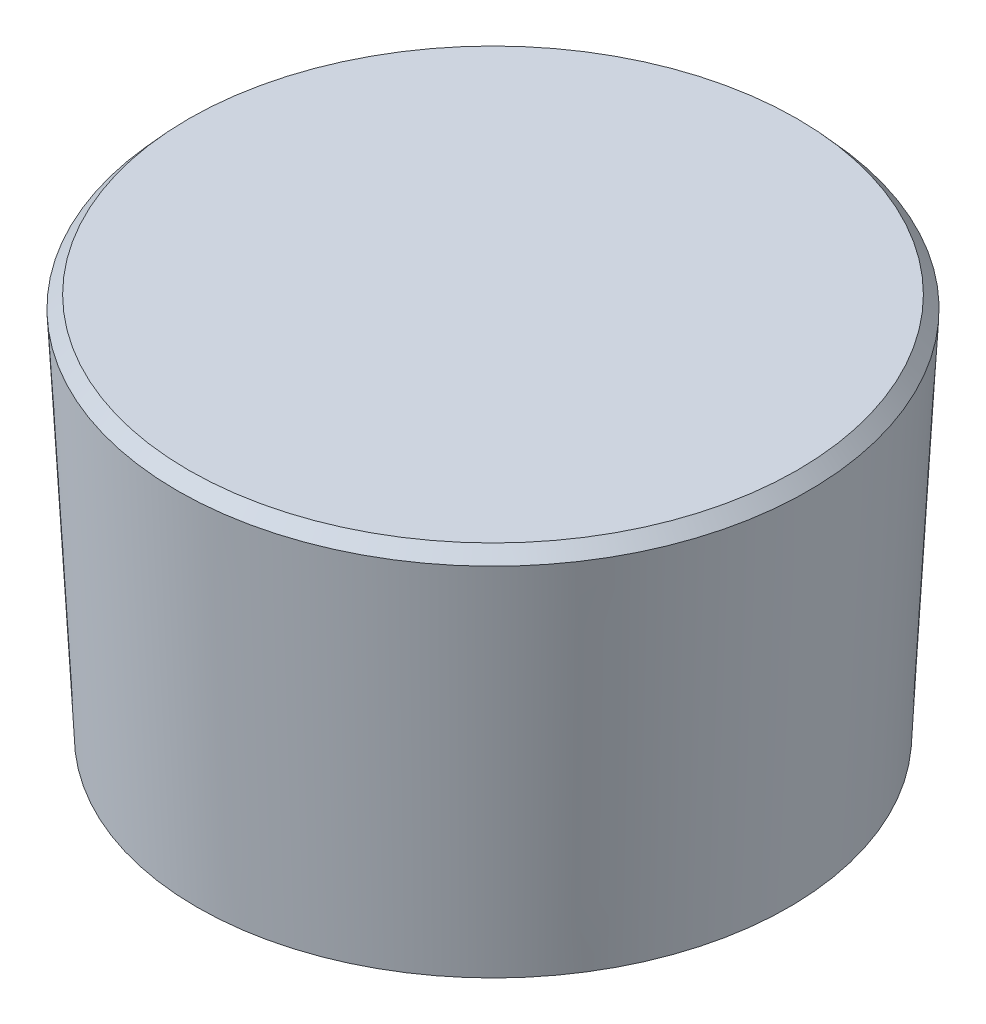
SolidWorks part; units mm, degrees
ref_plane "Front" through (0, 0, 0) normal (0, 0, 1) x (1, 0, 0)
ref_plane "Top" through (0, 0, 0) normal (0, 1, 0) x (1, 0, 0)
ref_plane "Right" through (0, 0, 0) normal (1, 0, 0) x (0, 0, -1)
sketch "Sketch1" plane through (0, 0, 0) normal (0, 1, 0) x (1, 0, 0)
  circle A0 centre (0, 0) radius 5.122
  dimension "D1" = 10.244
extrude "Extrude1" add sketch "Sketch1" against normal blind 6.2 draft 3
chamfer "Chamfer1" distance 0.2 angle 45 1 edges at (0, 0, 5.122)
